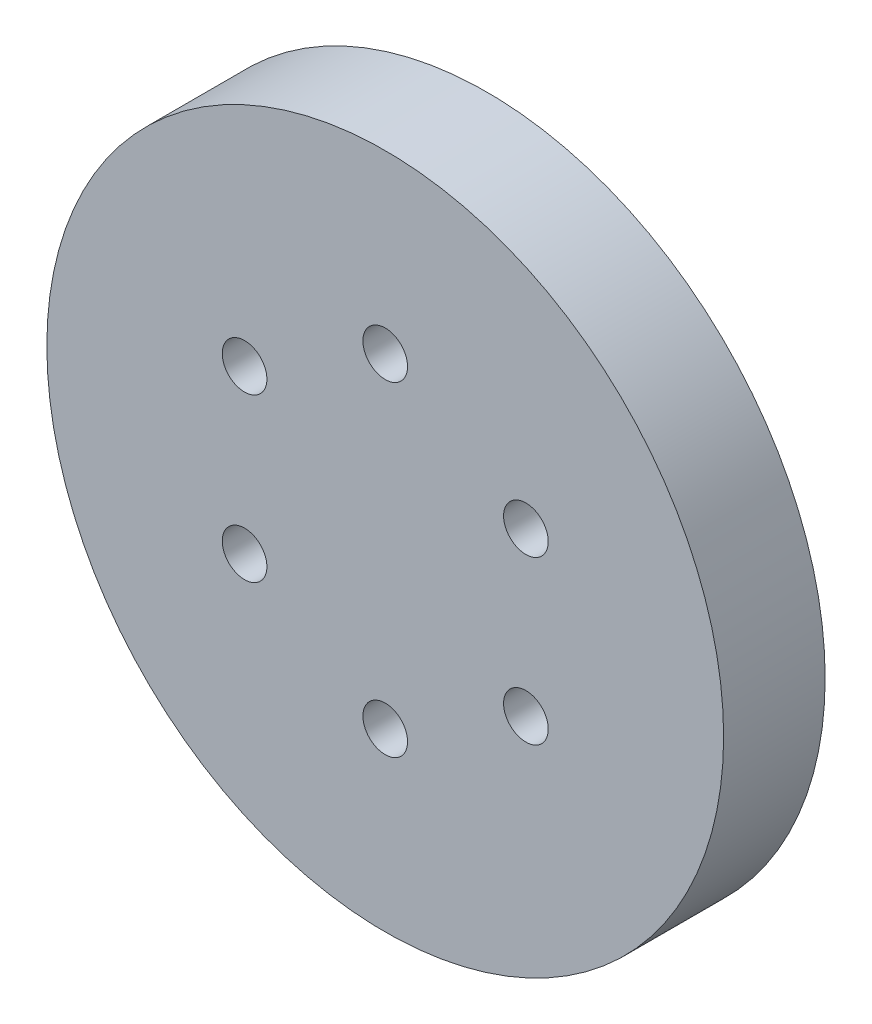
SolidWorks part; units mm, degrees
material "6061 合金"
ref_plane "前视基准面" through (0, 0, 0) normal (0, 0, 1) x (1, 0, 0)
ref_plane "上视基准面" through (0, 0, 0) normal (0, 1, 0) x (1, 0, 0)
ref_plane "右视基准面" through (0, 0, 0) normal (1, 0, 0) x (0, 0, -1)
other "Configuration Table"
sketch "草图1" plane through (0, 0, 0) normal (0, 0, 1) x (1, 0, 0)
  circle A0 centre (0, 0) radius 12 construction
  circle A1 centre (0, 12) radius 1.65
  circle A2 centre (10.3923, 6) radius 1.65
  circle A3 centre (10.3923, -6) radius 1.65
  circle A4 centre (0, -12) radius 1.65
  circle A5 centre (-10.3923, -6) radius 1.65
  circle A6 centre (-10.3923, 6) radius 1.65
  circle A7 centre (0, 0) radius 25
  point P17 (0, 0)
  dimension "D2" = 3.3
  dimension "D4" = 50
  dimension "D3" = 6
extrude "凸台-拉伸1" add sketch "草图1" along normal blind 7.5
sketch3d "3D草图1"
  point P0 (-6.6814, 17.1609, 7.5)
sketch3d "3D草图2"
  point P0 (-15.2718, 13.0248, 7.5)
ref_plane "基准面2" through (0, 0, 7.5) normal (0, 0, 1) x (1, 0, 0)
sketch "草图3" plane through (0, 0, 7.5) normal (0, 0, 1) x (1, 0, 0)
  circle A0 centre (0, 12) radius 3
  circle A1 centre (10.3923, 6) radius 3
  circle A2 centre (10.3923, -6) radius 3
  circle A3 centre (0, -12) radius 3
  circle A4 centre (-10.3923, -6) radius 3
  circle A5 centre (-10.3923, 6) radius 3
  point P15 (0, 0)
  dimension "D1" = 6
